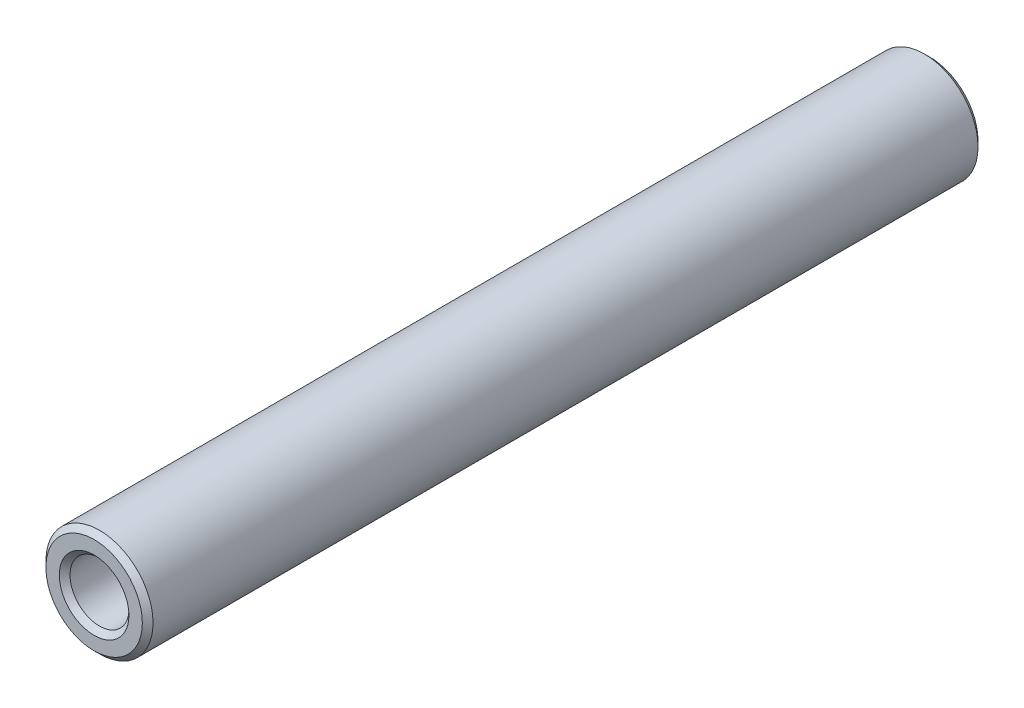
SolidWorks part; units mm, degrees
material "AISI 4140 Steel, quenched & tempered"
ref_plane "Front Plane" through (0, 0, 0) normal (1, 0, 0) x (0, 1, 0)
ref_plane "Top Plane" through (0, 0, 0) normal (0, 0, 1) x (0, 1, 0)
ref_plane "Right Plane" through (0, 0, 0) normal (0, 1, 0) x (-1, 0, 0)
sketch "Sketch1" plane through (0, 0, 0) normal (0, 0, 1) x (0, 1, 0)
  circle A0 centre (0, 0) radius 5
  circle A1 centre (0, 0) radius 2.75
  dimension "D1" = 10
  dimension "D2" = 5.5
extrude "Boss-Extrude1" add sketch "Sketch1" along normal mid plane 78
chamfer "Chamfer1" distance 0.5 angle 45 2 edges at (2.75, 0, -39) (2.75, 0, 39)
chamfer "Chamfer2" distance 0.5 angle 45 2 edges at (5, 0, 39) (5, 0, -39)
